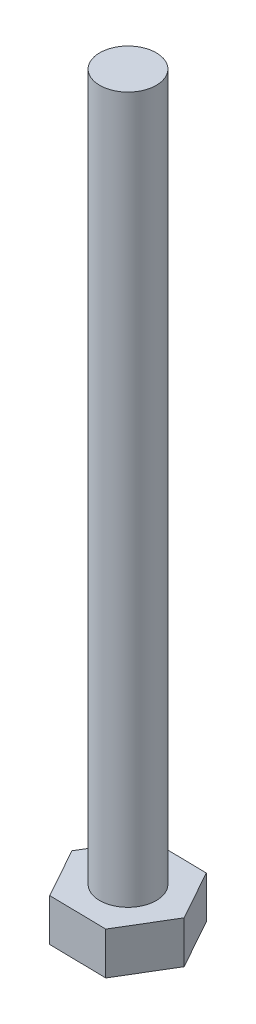
SolidWorks part; units mm, degrees
ref_plane "Front Plane" through (0, 0, 0) normal (0, 0, 1) x (1, 0, 0)
ref_plane "Top Plane" through (0, 0, 0) normal (0, 1, 0) x (1, 0, 0)
ref_plane "Right Plane" through (0, 0, 0) normal (1, 0, 0) x (0, 0, -1)
sketch "Sketch1" plane through (0, 0, 0) normal (0, 1, 0) x (1, 0, 0)
  line L1 (1.9591, -3.5349) -> (4.0408, -0.0708)
  line L2 (4.0408, -0.0708) -> (2.0817, 3.4641)
  line L3 (2.0817, 3.4641) -> (-1.9591, 3.5349)
  line L4 (-1.9591, 3.5349) -> (-4.0408, 0.0708)
  line L5 (-4.0408, 0.0708) -> (-2.0817, -3.4641)
  line L6 (-2.0817, -3.4641) -> (1.9591, -3.5349)
  circle A0 centre (0, 0) radius 3.5 construction
  dimension "D1" = 7
extrude "Boss-Extrude1" add sketch "Sketch1" along normal blind 3
sketch "Sketch2" plane through (0, 3, 0) normal (0, 1, 0) x (1, 0, 0)
  circle A0 centre (0, 0) radius 2
  dimension "D1" = 4
extrude "Boss-Extrude2" add sketch "Sketch2" along normal blind 50
